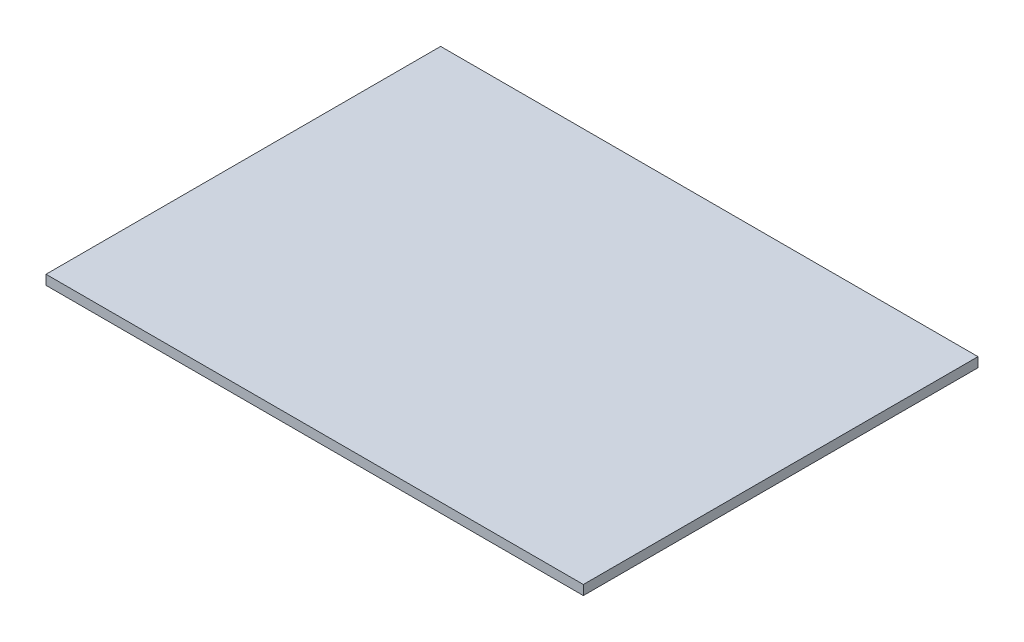
SolidWorks part; units mm, degrees
ref_plane "Front Plane" through (0, 0, 0) normal (0, 0, 1) x (1, 0, 0)
ref_plane "Top Plane" through (0, 0, 0) normal (0, 1, 0) x (1, 0, 0)
ref_plane "Right Plane" through (0, 0, 0) normal (1, 0, 0) x (0, 0, -1)
sketch "Sketch1" plane through (0, 0, 0) normal (0, 1, 0) x (1, 0, 0)
  line L0 (0, 0) -> (0, 104.0609)
  line L1 (0, 104.0609) -> (-141.6942, 104.0609)
  line L2 (-141.6942, 104.0609) -> (-141.6942, 0)
  line L3 (-141.6942, 0) -> (0, 0)
extrude "Boss-Extrude1" add sketch "Sketch1" along normal blind 2.54
